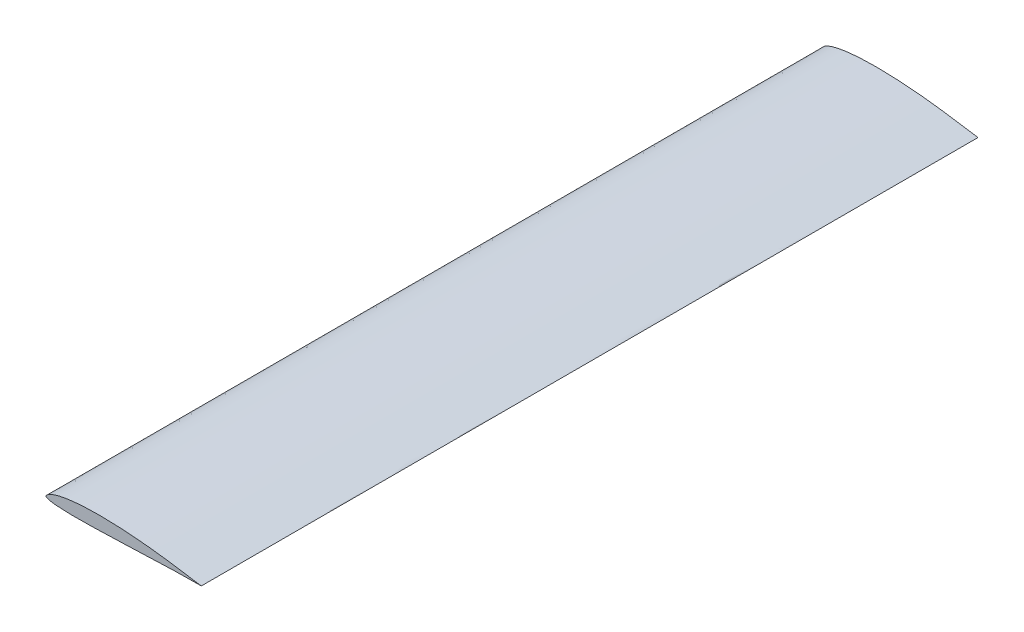
SolidWorks part; units mm, degrees
ref_plane "Front Plane" through (0, 0, 0) normal (0, 0, 1) x (1, 0, 0)
ref_plane "Top Plane" through (0, 0, 0) normal (0, 1, 0) x (1, 0, 0)
ref_plane "Right Plane" through (0, 0, 0) normal (1, 0, 0) x (0, 0, -1)
curve "Curve1"
  spline degree 3 poles (49.6515, 0.009, 0) (50.0884, -0.0053, 0) (49.6522, 0.033, 0) (49.3011, 0.0832, 0) (48.4593, 0.1945, 0) (47.4415, 0.3499, 0) (46.1338, 0.5549, 0) (44.6155, 0.7993, 0) (42.8923, 1.0751, 0) (40.9958, 1.371, 0) (38.9477, 1.6747, 0) (36.7703, 1.9711, 0) (34.4838, 2.2498, 0) (32.109, 2.5048, 0) (29.6686, 2.7322, 0) (27.1889, 2.9318, 0) (24.6971, 3.0996, 0) (22.2188, 3.2252, 0) (19.7784, 3.3048, 0) (17.3996, 3.3388, 0) (15.1043, 3.321, 0) (12.9138, 3.2492, 0) (10.8475, 3.1296, 0) (8.9245, 2.9596, 0) (7.1613, 2.7404, 0) (5.5715, 2.4767, 0) (4.1671, 2.1739, 0) (2.9576, 1.8376, 0) (1.9505, 1.4773, 0) (1.1488, 1.103, 0) (0.5587, 0.7311, 0) (0.2281, 0.4366, 0) (0.09, 0.2394, 0) (0.0408, 0.1522, 0) (0.0104, 0.0738, 0) (-0.0015, 0.012, 0) (0.0009, -0.0367, 0) (0.0247, -0.0804, 0) (0.0694, -0.1305, 0) (0.1411, -0.1885, 0) (0.3144, -0.2962, 0) (0.7005, -0.4536, 0) (1.3781, -0.6282, 0) (2.3375, -0.7877, 0) (3.539, -0.9182, 0) (4.9742, -1.0154, 0) (6.6312, -1.0793, 0) (8.4956, -1.1107, 0) (10.5497, -1.112, 0) (12.7728, -1.0868, 0) (15.1414, -1.0389, 0) (17.6298, -0.9723, 0) (20.2103, -0.8906, 0) (22.8538, -0.7976, 0) (25.5303, -0.6969, 0) (28.2091, -0.5925, 0) (30.859, -0.4876, 0) (33.449, -0.3866, 0) (35.9478, -0.2924, 0) (38.325, -0.208, 0) (40.551, -0.1358, 0) (42.5964, -0.0785, 0) (44.4361, -0.0365, 0) (46.0378, -0.0091, 0) (47.399, 0.0043, 0) (48.4441, 0.0096, 0) (49.2972, 0.0042, 0) (49.6515, 0.009, 0) (50.0884, -0.0053, 0) (49.6522, 0.033, 0) knots -0.014204 -0.006419 -0.001632 0 0.001631 0.006435 0.014221 0.024766 0.037827 0.053149 0.070474 0.089536 0.110075 0.13186 0.154693 0.178371 0.20268 0.227364 0.252133 0.276728 0.300939 0.324527 0.347267 0.368992 0.389507 0.408628 0.426224 0.442179 0.456396 0.468805 0.479372 0.488086 0.494968 0.500034 0.501036 0.502094 0.502997 0.503513 0.503956 0.504409 0.504955 0.505943 0.50713 0.510998 0.518232 0.527846 0.539809 0.554056 0.57049 0.588974 0.609342 0.631393 0.654894 0.67959 0.705203 0.731447 0.75802 0.78462 0.810936 0.836657 0.861473 0.885081 0.907188 0.927507 0.945765 0.961712 0.975122 0.985796 0.993581 0.998368 1 1.001631 1.006435 1.014221 periodic
sketch "Sketch1" plane through (0, 0, 0) normal (0, 0, 1) x (1, 0, 0)
  spline S0 degree 3 poles (49.6515, 0.009) (50.0884, -0.0053) (49.6522, 0.033) (49.3011, 0.0832) (48.4593, 0.1945) (47.4415, 0.3499) (46.1338, 0.5549) (44.6155, 0.7993) (42.8923, 1.0751) (40.9958, 1.371) (38.9477, 1.6747) (36.7703, 1.9711) (34.4838, 2.2498) (32.109, 2.5048) (29.6686, 2.7322) (27.1889, 2.9318) (24.6971, 3.0996) (22.2188, 3.2252) (19.7784, 3.3048) (17.3996, 3.3388) (15.1043, 3.321) (12.9138, 3.2492) (10.8475, 3.1296) (8.9245, 2.9596) (7.1613, 2.7404) (5.5715, 2.4767) (4.1671, 2.1739) (2.9576, 1.8376) (1.9505, 1.4773) (1.1488, 1.103) (0.5587, 0.7311) (0.2281, 0.4366) (0.09, 0.2394) (0.0408, 0.1522) (0.0104, 0.0738) (-0.0015, 0.012) (0.0009, -0.0367) (0.0247, -0.0804) (0.0694, -0.1305) (0.1411, -0.1885) (0.3144, -0.2962) (0.7005, -0.4536) (1.3781, -0.6282) (2.3375, -0.7877) (3.539, -0.9182) (4.9742, -1.0154) (6.6312, -1.0793) (8.4956, -1.1107) (10.5497, -1.112) (12.7728, -1.0868) (15.1414, -1.0389) (17.6298, -0.9723) (20.2103, -0.8906) (22.8538, -0.7976) (25.5303, -0.6969) (28.2091, -0.5925) (30.859, -0.4876) (33.449, -0.3866) (35.9478, -0.2924) (38.325, -0.208) (40.551, -0.1358) (42.5964, -0.0785) (44.4361, -0.0365) (46.0378, -0.0091) (47.399, 0.0043) (48.4441, 0.0096) (49.2972, 0.0042) (49.6515, 0.009) (50.0884, -0.0053) (49.6522, 0.033) knots -0.014204 -0.006419 -0.001632 0 0.001631 0.006435 0.014221 0.024766 0.037827 0.053149 0.070474 0.089536 0.110075 0.13186 0.154693 0.178371 0.20268 0.227364 0.252133 0.276728 0.300939 0.324527 0.347267 0.368992 0.389507 0.408628 0.426224 0.442179 0.456396 0.468805 0.479372 0.488086 0.494968 0.500034 0.501036 0.502094 0.502997 0.503513 0.503956 0.504409 0.504955 0.505943 0.50713 0.510998 0.518232 0.527846 0.539809 0.554056 0.57049 0.588974 0.609342 0.631393 0.654894 0.67959 0.705203 0.731447 0.75802 0.78462 0.810936 0.836657 0.861473 0.885081 0.907188 0.927507 0.945765 0.961712 0.975122 0.985796 0.993581 0.998368 1 1.001631 1.006435 1.014221 only from (50, 0) to (50, 0) construction
  spline S1 degree 3 poles (49.6515, 0.009) (50.0884, -0.0053) (49.6522, 0.033) (49.3011, 0.0832) (48.4593, 0.1945) (47.4415, 0.3499) (46.1338, 0.5549) (44.6155, 0.7993) (42.8923, 1.0751) (40.9958, 1.371) (38.9477, 1.6747) (36.7703, 1.9711) (34.4838, 2.2498) (32.109, 2.5048) (29.6686, 2.7322) (27.1889, 2.9318) (24.6971, 3.0996) (22.2188, 3.2252) (19.7784, 3.3048) (17.3996, 3.3388) (15.1043, 3.321) (12.9138, 3.2492) (10.8475, 3.1296) (8.9245, 2.9596) (7.1613, 2.7404) (5.5715, 2.4767) (4.1671, 2.1739) (2.9576, 1.8376) (1.9505, 1.4773) (1.1488, 1.103) (0.5587, 0.7311) (0.2281, 0.4366) (0.09, 0.2394) (0.0408, 0.1522) (0.0104, 0.0738) (-0.0015, 0.012) (0.0009, -0.0367) (0.0247, -0.0804) (0.0694, -0.1305) (0.1411, -0.1885) (0.3144, -0.2962) (0.7005, -0.4536) (1.3781, -0.6282) (2.3375, -0.7877) (3.539, -0.9182) (4.9742, -1.0154) (6.6312, -1.0793) (8.4956, -1.1107) (10.5497, -1.112) (12.7728, -1.0868) (15.1414, -1.0389) (17.6298, -0.9723) (20.2103, -0.8906) (22.8538, -0.7976) (25.5303, -0.6969) (28.2091, -0.5925) (30.859, -0.4876) (33.449, -0.3866) (35.9478, -0.2924) (38.325, -0.208) (40.551, -0.1358) (42.5964, -0.0785) (44.4361, -0.0365) (46.0378, -0.0091) (47.399, 0.0043) (48.4441, 0.0096) (49.2972, 0.0042) (49.6515, 0.009) (50.0884, -0.0053) (49.6522, 0.033) knots -0.014204 -0.006419 -0.001632 0 0.001631 0.006435 0.014221 0.024766 0.037827 0.053149 0.070474 0.089536 0.110075 0.13186 0.154693 0.178371 0.20268 0.227364 0.252133 0.276728 0.300939 0.324527 0.347267 0.368992 0.389507 0.408628 0.426224 0.442179 0.456396 0.468805 0.479372 0.488086 0.494968 0.500034 0.501036 0.502094 0.502997 0.503513 0.503956 0.504409 0.504955 0.505943 0.50713 0.510998 0.518232 0.527846 0.539809 0.554056 0.57049 0.588974 0.609342 0.631393 0.654894 0.67959 0.705203 0.731447 0.75802 0.78462 0.810936 0.836657 0.861473 0.885081 0.907188 0.927507 0.945765 0.961712 0.975122 0.985796 0.993581 0.998368 1 1.001631 1.006435 1.014221 only from (50, 0) to (50, 0)
extrude "Boss-Extrude1" add sketch "Sketch1" along normal blind 250
